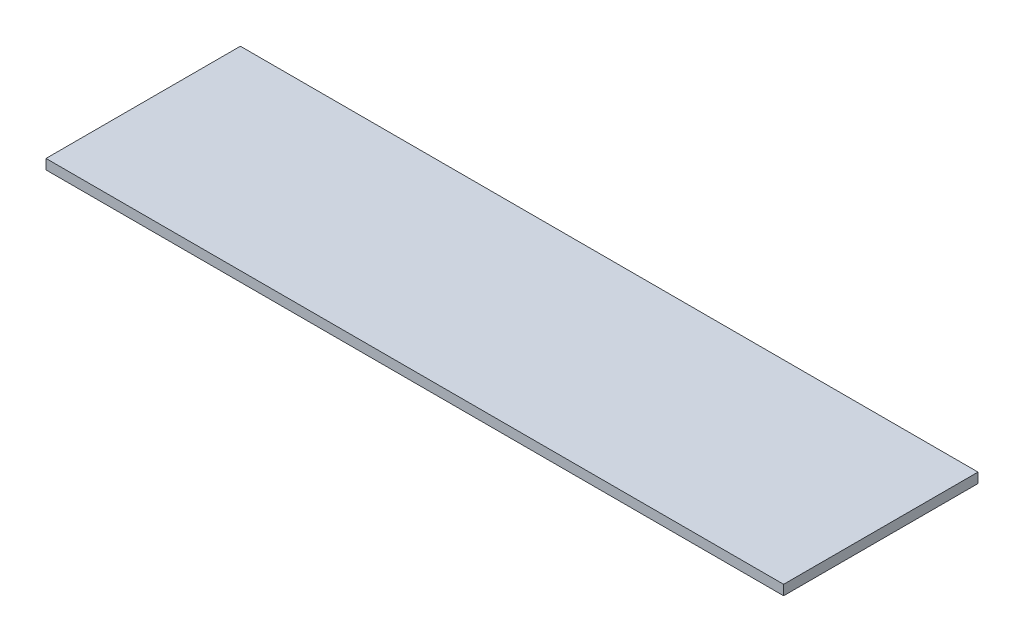
SolidWorks part; units mm, degrees
ref_plane "Front Plane" through (0, 0, 0) normal (0, 0, 1) x (1, 0, 0)
ref_plane "Top Plane" through (0, 0, 0) normal (0, 1, 0) x (1, 0, 0)
ref_plane "Right Plane" through (0, 0, 0) normal (1, 0, 0) x (0, 0, -1)
sketch "Sketch1" plane through (0, 0, 0) normal (0, 1, 0) x (1, 0, 0)
  line L1 (-58.7504, 21.2331) -> (411.1496, 21.2331)
  line L2 (-58.7504, 21.2331) -> (-58.7504, -102.5919)
  line L3 (-58.7504, -102.5919) -> (411.1496, -102.5919)
  line L4 (411.1496, 21.2331) -> (411.1496, -102.5919)
  dimension "D1" = 469.9
  dimension "D2" = 123.825
extrude "Boss-Extrude1" add sketch "Sketch1" against normal blind 6.35
